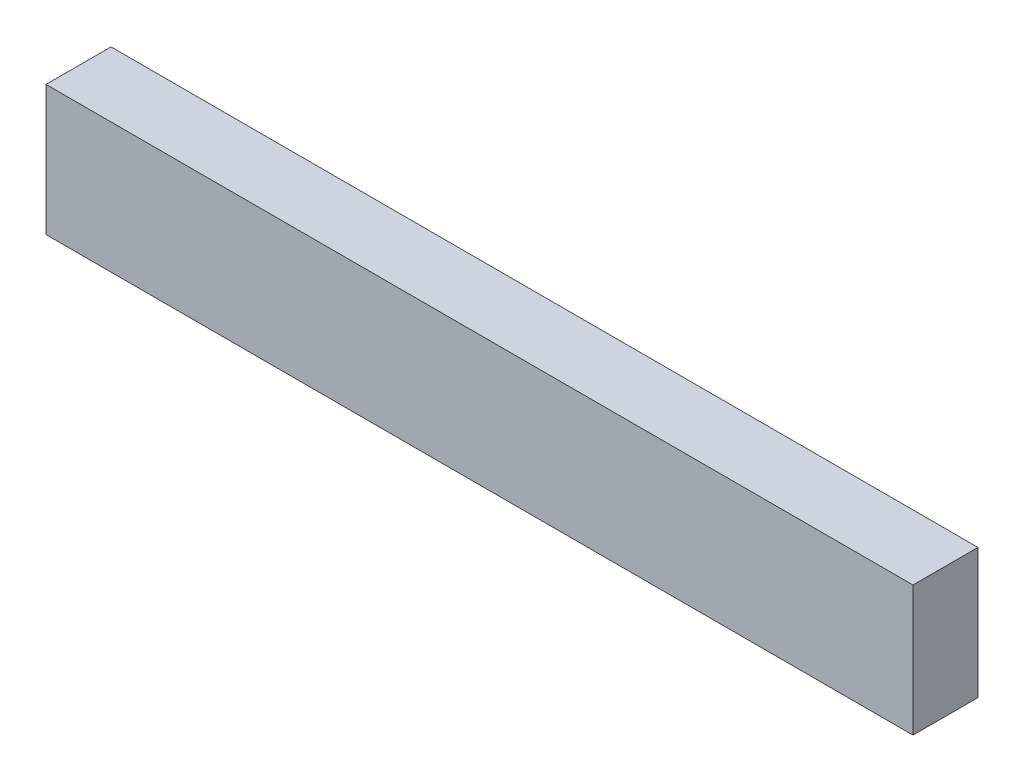
SolidWorks part; units mm, degrees
ref_plane "前视基准面" through (0, 0, 0) normal (0, 0, 1) x (1, 0, 0)
ref_plane "上视基准面" through (0, 0, 0) normal (0, 1, 0) x (1, 0, 0)
ref_plane "右视基准面" through (0, 0, 0) normal (1, 0, 0) x (0, 0, -1)
other "Configuration Table"
sketch "草图1" plane through (0, 0, 0) normal (0, 1, 0) x (1, 0, 0)
  line L1 (-40, 3) -> (40, 3)
  line L2 (-40, 3) -> (-40, -3)
  line L3 (-40, -3) -> (40, -3)
  line L4 (40, 3) -> (40, -3)
  line L5 (-40, 3) -> (40, -3) construction
  line L6 (-40, -3) -> (40, 3) construction
  point P0 (0, 0)
  dimension "D1" = 6
  dimension "D2" = 80
extrude "凸台-拉伸1" add sketch "草图1" along normal blind 12
